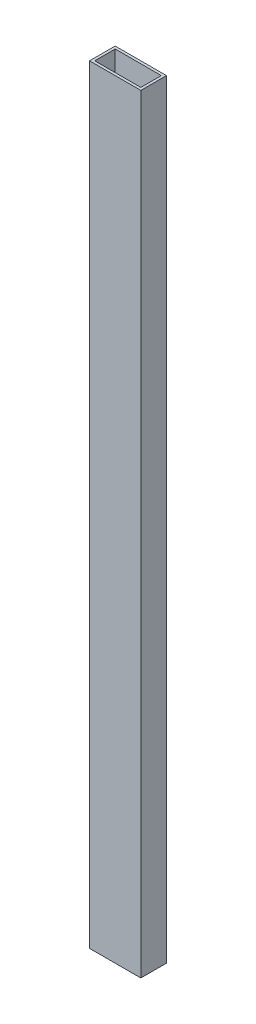
SolidWorks part; units mm, degrees
ref_plane "Front Plane" through (0, 0, 0) normal (0, 0, 1) x (1, 0, 0)
ref_plane "Top Plane" through (0, 0, 0) normal (0, 1, 0) x (1, 0, 0)
ref_plane "Right Plane" through (0, 0, 0) normal (1, 0, 0) x (0, 0, -1)
sketch "Sketch1" plane through (0, 0, 0) normal (0, 1, 0) x (1, 0, 0)
  line L1 (0, 0) -> (50.8, 0)
  line L2 (0, 0) -> (0, 25.4)
  line L3 (0, 25.4) -> (50.8, 25.4)
  line L4 (50.8, 0) -> (50.8, 25.4)
  dimension "D1" = 50.8
  dimension "D2" = 25.4
extrude "Boss-Extrude1" add sketch "Sketch1" along normal blind 762
sketch "Sketch2" plane through (0, 762, 0) normal (0, 1, 0) x (1, 0, 0)
  line L0 (25.4, 0) -> (25.4, 25.4) construction
  line L1 (0, 0) -> (50.8, 0) construction
  line L2 (50.8, 25.4) -> (0, 25.4) construction
  line L3 (50.8, 0) -> (50.8, 25.4) construction
  line L4 (50.8, 12.7) -> (0, 12.7) construction
  line L5 (0, 25.4) -> (0, 0) construction
  line L6 (50.8, 12.7) -> (48.26, 12.7) construction
  line L7 (25.4, 0) -> (25.4, 2.54) construction
  line L9 (2.54, 22.86) -> (48.26, 22.86)
  line L10 (2.54, 22.86) -> (2.54, 2.54)
  line L11 (2.54, 2.54) -> (48.26, 2.54)
  line L12 (48.26, 22.86) -> (48.26, 2.54)
  line L13 (2.54, 22.86) -> (48.26, 2.54) construction
  line L14 (2.54, 2.54) -> (48.26, 22.86) construction
  point P14 (25.4, 12.7)
extrude "Cut-Extrude1" cut sketch "Sketch2" against normal blind 762
